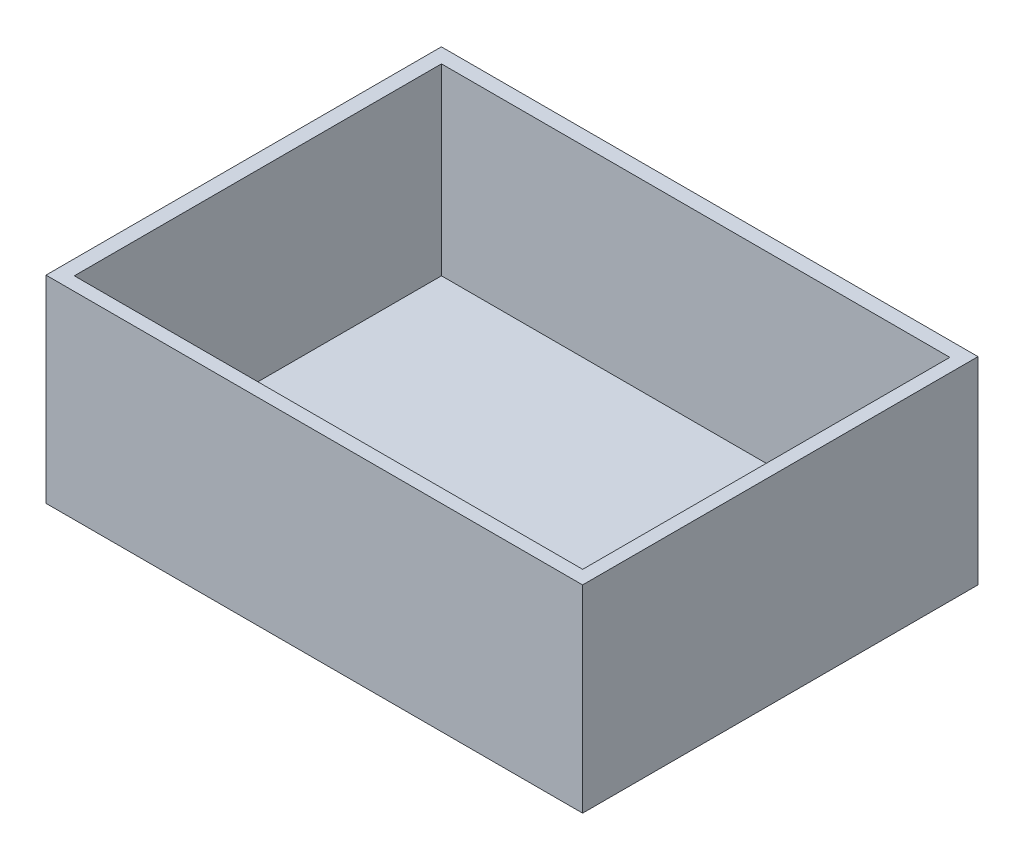
SolidWorks part; units mm, degrees
ref_plane "Front Plane" through (0, 0, 0) normal (0, 0, 1) x (1, 0, 0)
ref_plane "Top Plane" through (0, 0, 0) normal (0, 1, 0) x (1, 0, 0)
ref_plane "Right Plane" through (0, 0, 0) normal (1, 0, 0) x (0, 0, -1)
sketch "Sketch2" plane through (0, 0, 0) normal (0, 1, 0) x (1, 0, 0)
  line L1 (-61.7895, 61.8947) -> (128.2105, 61.8947)
  line L2 (-61.7895, 61.8947) -> (-61.7895, -78.1053)
  line L3 (-61.7895, -78.1053) -> (128.2105, -78.1053)
  line L4 (128.2105, 61.8947) -> (128.2105, -78.1053)
  dimension "D1" = 140
  dimension "D2" = 190
extrude "Boss-Extrude1" add sketch "Sketch2" along normal blind 70
sketch "Sketch3" plane through (0, 70, 0) normal (0, 1, 0) x (1, 0, 0)
  line L1 (-56.5546, 56.6885) -> (123.4454, 56.6885)
  line L2 (-56.5546, 56.6885) -> (-56.5546, -73.3115)
  line L3 (-56.5546, -73.3115) -> (123.4454, -73.3115)
  line L4 (123.4454, 56.6885) -> (123.4454, -73.3115)
  dimension "D1" = 180
  dimension "D2" = 130
extrude "Cut-Extrude1" cut sketch "Sketch3" against normal blind 65
